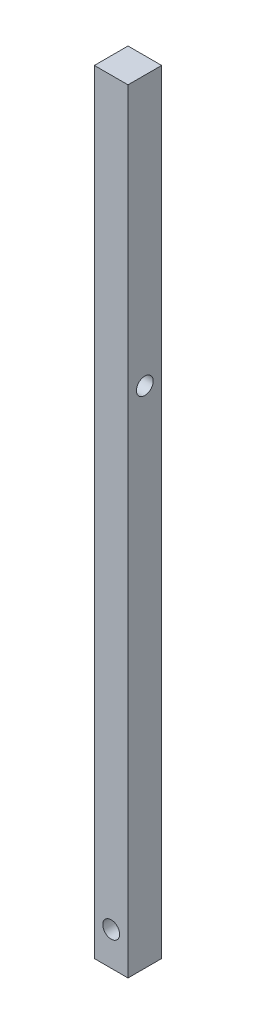
SolidWorks part; units mm, degrees
material "6061 Alloy"
ref_plane "Front Plane" through (0, 0, 0) normal (0, 0, 1) x (1, 0, 0)
ref_plane "Top Plane" through (0, 0, 0) normal (0, 1, 0) x (1, 0, 0)
ref_plane "Right Plane" through (0, 0, 0) normal (1, 0, 0) x (0, 0, -1)
sketch "Sketch1" plane through (0, 0, 0) normal (0, 1, 0) x (1, 0, 0)
  line L1 (-5, 5) -> (5, 5)
  line L2 (-5, 5) -> (-5, -5)
  line L3 (-5, -5) -> (5, -5)
  line L4 (5, 5) -> (5, -5)
  line L5 (-5, 5) -> (5, -5) construction
  line L6 (-5, -5) -> (5, 5) construction
  point P0 (0, 0)
  dimension "D1" = 10
  dimension "D2" = 10
extrude "Boss-Extrude1" add sketch "Sketch1" along normal blind 300
sketch "Sketch3" plane through (-5, 0, 0) normal (-1, 0, 0) x (0, 0, 1)
  line L0 (-5, 300) -> (5, 300) construction
  line L1 (5, 300) -> (5, 0) construction
  circle A0 centre (0, 150) radius 2.5
  point P4 (0, 300)
  point P7 (5, 150)
  dimension "D1" = 5
extrude "Cut-Extrude1" cut sketch "Sketch3" against normal through all
sketch "Sketch4" plane through (0, 300, 0) normal (0, 1, 0) x (1, 0, 0)
  line L1 (-5, 5) -> (5, 5)
  line L2 (-5, 5) -> (-5, -5)
  line L3 (-5, -5) -> (5, -5)
  line L4 (5, 5) -> (5, -5)
  line L5 (-5, 5) -> (5, -5) construction
  line L6 (-5, -5) -> (5, 5) construction
  point P0 (0, 0)
extrude "Cut-Extrude2" cut sketch "Sketch4" against normal blind 70
sketch "Sketch5" plane through (0, 0, -5) normal (0, 0, -1) x (-1, 0, 0)
  line L0 (-5, 0) -> (5, 0) construction
  circle A0 centre (0, 10) radius 2.5
  point P5 (0, 0)
  dimension "D1" = 5
  dimension "D2" = 10
extrude "Cut-Extrude3" cut sketch "Sketch5" against normal through all
